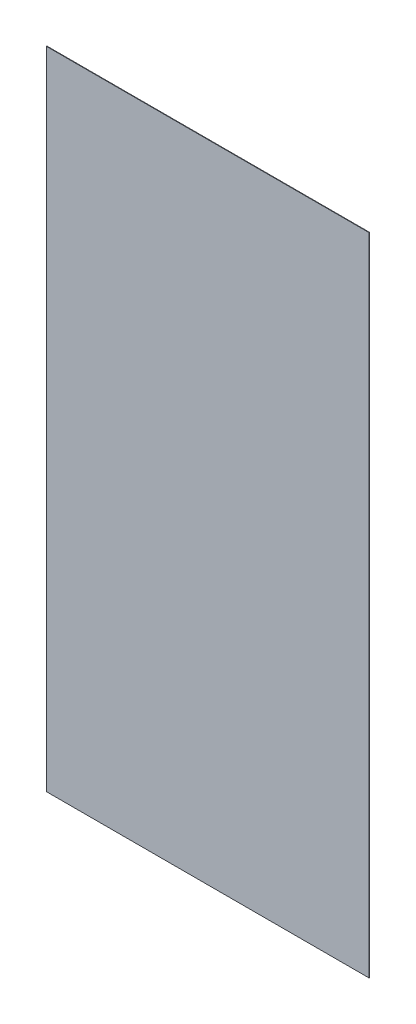
SolidWorks part; units mm, degrees
ref_plane "Alzado" through (0, 0, 0) normal (0, 0, 1) x (1, 0, 0)
ref_plane "Planta" through (0, 0, 0) normal (0, 1, 0) x (1, 0, 0)
ref_plane "Vista lateral" through (0, 0, 0) normal (1, 0, 0) x (0, 0, -1)
sketch "Croquis1" plane through (0, 0, 0) normal (0, 0, 1) x (1, 0, 0)
  line L1 (0, 0) -> (1220, 0)
  line L2 (0, 0) -> (0, -2440)
  line L3 (0, -2440) -> (1220, -2440)
  line L4 (1220, 0) -> (1220, -2440)
  dimension "D1" = 2440
  dimension "D2" = 1220
extrude "Saliente-Extruir1" add sketch "Croquis1" along normal blind 1.9
